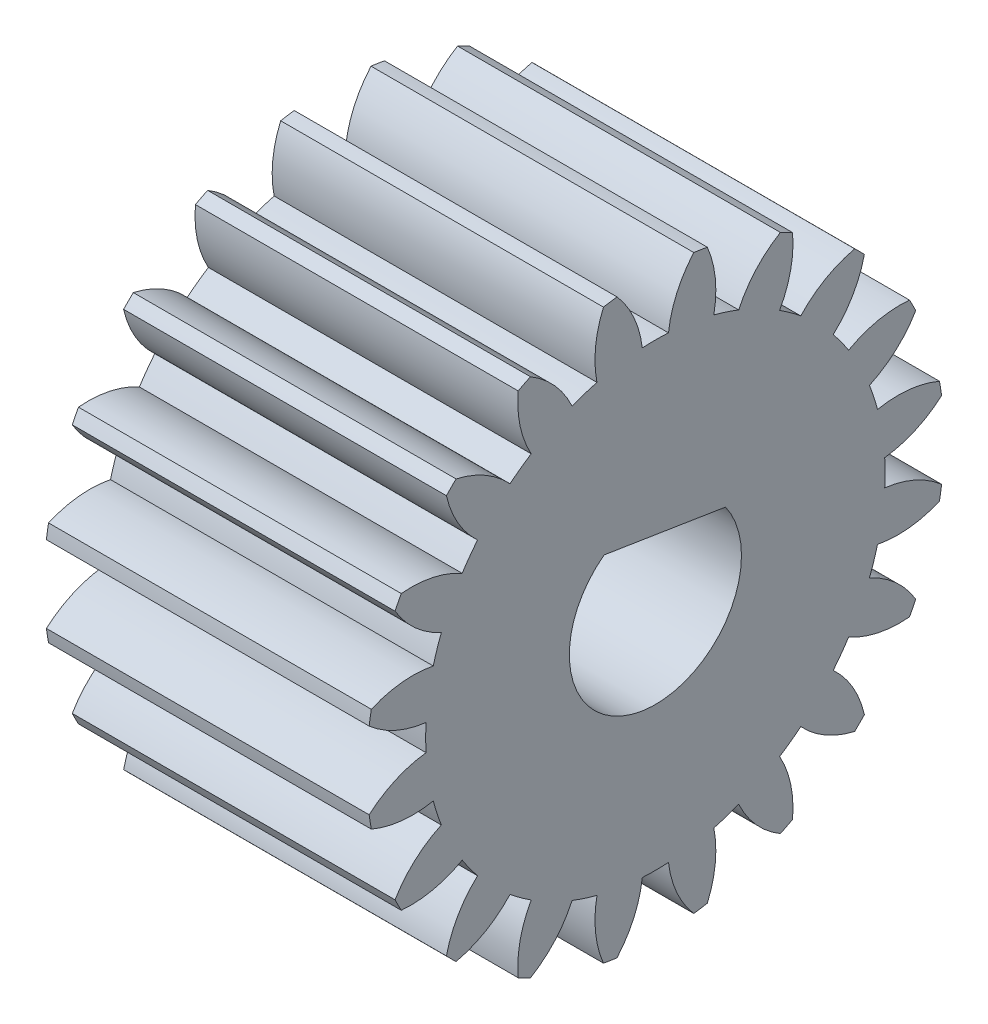
SolidWorks part; units mm, degrees
ref_plane "Plane1" through (0, 0, 0) normal (0, 0, 1) x (1, 0, 0)
ref_plane "Plane2" through (0, 0, 0) normal (0, 1, 0) x (1, 0, 0)
ref_plane "Plane3" through (0, 0, 0) normal (1, 0, 0) x (0, 0, -1)
sketch "HoldingSke" plane through (0, 0, 0) normal (0, 1, 0) x (1, 0, 0)
  line L0 (0, 0) -> (0.7702, -0.2803)
  line L1 (-15, 0) -> (100, 0) construction
  line L2 (0, 0) -> (-2.1039, 2.3779)
  line L3 (0, 0) -> (-11.863, 4.5341)
  line L4 (0, 0) -> (8.1152, 2.9537)
  line L5 (0, 0) -> (-46.8476, -17.4728)
  line L6 (0, 0) -> (-12.4344, -8.3896)
  line L7 (-2.1039, 2.3779) -> (8.6586, 51.2059)
  line L8 (-76.2, 54.61) -> (-74.8, 54.61)
  line L9 (-71.009, 38.7566) -> (-53.1078, 45.2721)
  line L10 (-76.2, 71.12) -> (104.1128, 71.12)
  line L11 (0, 0) -> (-15, 0)
  line L12 (-76.2, 101.6) -> (-76.155, 101.6)
  line L13 (24.9733, 27.94) -> (52.9518, 28.4284)
  line L14 (24.9733, 27.94) -> (24.9743, 27.94)
  line L15 (24.9733, 27.94) -> (100.4006, 29.5858)
  line L16 (-63.627, -1.22) -> (-12.827, -1.22)
  circle A0 centre (0, 0) radius 4
  circle A1 centre (0, 0) radius 10.674
  circle A2 centre (0, 0) radius 37.5
  circle A3 centre (0, 0) radius 4
  dimension "MHD" = 21.348
  dimension "Hub_dia" = 75
  dimension "Bore" = 8
  dimension "MBD" = 8
  dimension "Num_teeth" = 20
  dimension "Pitch" = 0.8197
  dimension "Overall_len" = 50
  dimension "Show_teeth" = 20
  dimension "Thickness" = 15
  dimension "OAL" = 50.0001
  dimension "T_dim" = 1.4
  dimension "Ap" = 20
  dimension "H" = 19.05
  dimension "Pitch_radius" = 180.3128
  dimension "Width" = 15
  dimension "Backlash" = 0.045
  dimension "Addendum_fac" = 1
  dimension "Dedendum_fac" = 1.25
  dimension "Clearance_fac" = 0.25
  dimension "Dedendum_add" = 0.001
  dimension "Module" = 1.22
sketch "BasProSke" plane through (0, 0, 0) normal (0, 1, 0) x (1, 0, 0)
  line L0 (-10, 0) -> (60, 0) construction
  line L1 (0, 0) -> (0, 13.42)
  line L2 (0, 0) -> (15, 0)
  line L3 (15, 0) -> (15, 13.42)
  line L4 (15, 13.42) -> (0, 13.42)
  dimension "Thickness" = 15
  dimension "Diameter" = 26.84
revolve "Base-Revolve" add sketch "BasProSke" angle 360 about L0
sketch "TooCutSke" plane through (0, 0, 0) normal (1, 0, 0) x (0, 0, -1)
  line L1 (0, 0) -> (0, 107) construction
  line L2 (0, 0) -> (-1.0359, 12.1559) construction
  line L3 (0, 0) -> (-3.8071, 24.037) construction
  line L4 (-1.0359, 12.1559) -> (-1.9035, 12.0185) construction
  arc A0 (0.6078, 10.6567) -> (-0.6078, 10.6567) centre (0, 0) ccw
  arc A1 (1.8049, 13.3237) -> (-1.8049, 13.3237) centre (0, 0) ccw
  circle A2 centre (0, 0) radius 12.2 construction
  circle A3 centre (0, 0) radius 11.4642 construction
  arc A4 (-0.6078, 10.6567) -> (-1.8049, 13.3237) centre (-5.4541, 10.0837) ccw
  arc A5 (1.8049, 13.3237) -> (0.6078, 10.6567) centre (5.4541, 10.0837) ccw
  dimension "Root_dia" = 21.348
  dimension "Overcut_dia" = 26.8908
  dimension "Pitch_dia" = 24.4
  dimension "Base_dia" = 22.9285
  dimension "Flank_rad" = 4.88
  dimension "Half_ang" = 9
  dimension "Half_CT" = 0.8785
extrude "ToothCut" cut sketch "TooCutSke" along normal through all
fillet "Breaks" [suppressed] radius 0.0244
fillet "RootFillets" [suppressed] radius 0.306
pattern_circular "TeethCuts" count 20 every 18 about axis through (-10, 0, 0) along (1, 0, 0) of "ToothCut", "RootFillets", "Breaks"
sketch "HubNeaOneSke" plane through (0, 0, 0) normal (-1, 0, 0) x (0, 0, 1)
  circle A0 centre (0, 0) radius 10.674
  dimension "Diameter" = 21.348
extrude "HubNearOne" [suppressed] add sketch "HubNeaOneSke" along normal blind 35.0001
sketch "HubNeaBotSke" plane through (0, 0, 0) normal (-1, 0, 0) x (0, 0, 1)
  circle A0 centre (0, 0) radius 10.674
  dimension "Diameter" = 21.348
extrude "HubNearBoth" [suppressed] add sketch "HubNeaBotSke" along normal blind 17.5
ref_plane "FarPln" through (15, 0, 0) normal (1, 0, 0) x (0, 0, -1)
sketch "HubFarSke" plane through (15, 0, 0) normal (1, 0, 0) x (0, 0, -1)
  circle A0 centre (0, 0) radius 10.674
  dimension "Diameter" = 21.348
extrude "HubFar" [suppressed] add sketch "HubFarSke" along normal blind 17.5
sketch "BorSke" plane through (0, 0, 0) normal (1, 0, 0) x (0, 0, -1)
  circle A0 centre (0, 0) radius 4
  dimension "Diameter" = 8
extrude "Bore" cut sketch "BorSke" along normal mid plane 100.0001
sketch "KeySke" plane through (0, 0, 0) normal (1, 0, 0) x (0, 0, -1)
  line L0 (-1.5, 0) -> (-1.5, 5.4)
  line L1 (-1.5, 5.4) -> (1.5, 5.4)
  line L2 (1.5, 5.4) -> (1.5, 0)
  line L3 (0, 0) -> (0, 34) construction
  line L4 (-1.5, 0) -> (1.5, 0)
  dimension "Offset" = 5.4
  dimension "Width" = 3
extrude "Keyway" [suppressed] cut sketch "KeySke" along normal mid plane 100.0001
pattern_circular "Keyway2" [suppressed] count 2 every 90 about axis through (-10, 0, 0) along (1, 0, 0)
sketch "Sketch1" plane through (0, 0, 0) normal (-1, 0, 0) x (0, 0, 1)
  line L0 (0, 0) -> (0, 4) construction
  line L1 (0, 0) -> (-0.438, 2.7655) construction
  line L2 (-0.438, 2.7655) -> (-0.6257, 3.9508) construction
  line L3 (-3.2594, 2.3187) -> (2.3834, 3.2124)
  circle A0 centre (0, 0) radius 4 construction
  arc A1 (-3.2594, 2.3187) -> (2.3834, 3.2124) centre (0, 0) cw
  point P9 (-0.438, 2.7655)
  dimension "D1" = 8
  dimension "D2" = 9
  dimension "D3" = 1.2
extrude "Boss-Extrude1" add sketch "Sketch1" against normal up to surface (15 mm away) up to face at (15, 0, 4)
sketch "Sketch2" plane through (0, 0, 0) normal (-1, 0, 0) x (0, 0, 1)
  line L0 (0, 0) -> (-7, 0) construction
  line L2 (-7.6, 4) -> (-6.4, 4)
  line L3 (-7.6, 4) -> (-7.6, -4)
  line L4 (-7.6, -4) -> (-6.4, -4)
  line L5 (-6.4, 4) -> (-6.4, -4)
  line L6 (-7.6, 4) -> (-6.4, -4) construction
  line L7 (-7.6, -4) -> (-6.4, 4) construction
  dimension "D1" = 7
  dimension "D2" = 8
  dimension "D3" = 1.2
extrude "Cut-Extrude1" cut sketch "Sketch2" against normal blind 2
equation "' \"Module@HoldingSke\" = 6.35"
equation "' \"Num_teeth@HoldingSke\" = 12"
equation "' \"Ap@HoldingSke\" =  20"
equation "' \"Ap@HoldingSke\" = 20"
equation "' \"Width@HoldingSke\" = 0.5 * 25.4"
equation "' \"Hub_dia@HoldingSke\"= 1 * 25.4"
equation "' \"Hub_dia@HoldingSke\" = 1 * 25.4"
equation "' \"Overall_len@HoldingSke\" = 1.0 * 25.4"
equation "' \"Bore@HoldingSke\" = 0.75 * 25.4"
equation "' \"T_dim@HoldingSke\" = 0.1 * 25.4"
equation "' \"Width@KeySke\" = 0.25 * 25.4"
equation "' \"Show_teeth@HoldingSke\" = 13"
equation "' \"Backlash@HoldingSke\" = 0.009 * 25.4"
equation "' \"Addendum_fac@HoldingSke\" = 1.0"
equation "' \"Dedendum_fac@HoldingSke\" = 1.25"
equation "' \"Dedendum_add@HoldingSke\" = 0.00005 * 25.4"
equation "' \"Clearance_fac@HoldingSke\" = 0.25"
equation "\"Pitch@HoldingSke\" = 1 / \"Module@HoldingSke\""
equation "\"Overcut_dia@TooCutSke\" = (\"Num_teeth@HoldingSke\" + 2 * \"Addendum_fac@HoldingSke\") / \"Pitch@HoldingSke\" + 0.002 * 25.4"
equation "\"Pitch_dia@TooCutSke\" = \"Num_teeth@HoldingSke\" / \"Pitch@HoldingSke\""
equation "\"Base_dia@TooCutSke\" = \"Num_teeth@HoldingSke\" / \"Pitch@HoldingSke\" * cos((\"Ap@HoldingSke\"  * 3.14159265 / 180))"
equation "\"Root_dia@TooCutSke\" = (\"Num_teeth@HoldingSke\" + 2) / \"Pitch@HoldingSke\" - 2 * (\"Addendum_fac@HoldingSke\" + \"Dedendum_fac@HoldingSke\") / \"Pitch@HoldingSke\" - \"Dedendum_add@HoldingSke\" * 2"
equation "\"Half_ang@TooCutSke\" = 180 / \"Num_teeth@HoldingSke\""
equation "\"Half_CT@TooCutSke\" = \"Num_teeth@HoldingSke\" / \"Pitch@HoldingSke\" * sin((3.14159265 / 2 / \"Num_teeth@HoldingSke\")) / 2 - 7 * \"Backlash@HoldingSke\" / 4"
equation "\"Flank_rad@TooCutSke\" = \"Num_teeth@HoldingSke\" / \"Pitch@HoldingSke\" / 5"
equation "\"Radius@RootFillets\" = \"Clearance_fac@HoldingSke\" / \"Pitch@HoldingSke\" + \"Dedendum_add@HoldingSke\""
equation "\"Break_rad@Breaks\" = 0.02 / \"Pitch@HoldingSke\""
equation "\"Thickness@HoldingSke\" = \"Width@HoldingSke\""
equation "\"OAL@HoldingSke\" = \"Thickness@HoldingSke\""
equation "\"MHD@HoldingSke\" = (\"Num_teeth@HoldingSke\" + 2) / \"Pitch@HoldingSke\" - 2 * (\"Addendum_fac@HoldingSke\" + \"Dedendum_fac@HoldingSke\")  / \"Pitch@HoldingSke\" - \"Dedendum_add@HoldingSke\" * 2"
equation "\"MBD@HoldingSke\" = (\"Num_teeth@HoldingSke\" + 2) / \"Pitch@HoldingSke\" - 2 * (\"Addendum_fac@HoldingSke\" + \"Dedendum_fac@HoldingSke\")  / \"Pitch@HoldingSke\" - \"Dedendum_add@HoldingSke\" * 2 - 0.002 * 25.4"
equation "\"MHD@HoldingSke\" = ((sgn( \"MHD@HoldingSke\" - \"Hub_dia@HoldingSke\" )-1)*( \"MHD@HoldingSke\" - \"Hub_dia@HoldingSke\" ))/-2+ \"Hub_dia@HoldingSke\""
equation "\"MBD@HoldingSke\" = ((sgn( \"MBD@HoldingSke\" - \"Bore@HoldingSke\" )-1)*( \"MBD@HoldingSke\" - \"Bore@HoldingSke\" ))/-2+ \"Bore@HoldingSke\""
equation "\"OAL@HoldingSke\" = ((sgn( \"OAL@HoldingSke\" - \"Overall_len@HoldingSke\" )+1)*( \"OAL@HoldingSke\" - \"Overall_len@HoldingSke\" ))/2 + \"Overall_len@HoldingSke\" + 0.000002 * 25.4"
equation "\"Num_teeth@TeethCuts\" = int( \"Show_teeth@HoldingSke\" ) + 1"
equation "\"Num_teeth@TeethCuts\" = ((sgn( \"Num_teeth@TeethCuts\" - \"Num_teeth@HoldingSke\" )-1)*( \"Num_teeth@TeethCuts\" - \"Num_teeth@HoldingSke\" ))/-2+ \"Num_teeth@HoldingSke\""
equation "\"Num_teeth@TeethCuts\" = ((sgn( \"Num_teeth@TeethCuts\" - 2.0)+1)*( \"Num_teeth@TeethCuts\" - 2.0))/2 +2.0"
equation "\"Angle@TeethCuts\" = 360.0 / \"Num_teeth@HoldingSke\""
equation "\"Diameter@BasProSke\" = (\"Num_teeth@HoldingSke\" + 2 * \"Addendum_fac@HoldingSke\") / \"Pitch@HoldingSke\""
equation "\"Thickness@BasProSke\"  = \"Thickness@HoldingSke\""
equation "' \"Fillet_rad@BasProSke\" =  \"Thickness@HoldingSke\" * 0.05"
equation "' \"Fillet_rad@BasProSke\" = \"Thickness@HoldingSke\" * 0.05"
equation "\"MHD@HoldingSke\" = ((sgn( \"MHD@HoldingSke\" - \"Root_dia@TooCutSke\" )-1)*( \"MHD@HoldingSke\" - \"Root_dia@TooCutSke\" ))/-2+ \"Root_dia@TooCutSke\""
equation "\"Diameter@HubNeaOneSke\" = \"MHD@HoldingSke\""
equation "\"Length@HubNearOne\" = \"OAL@HoldingSke\" - \"Thickness@BasProSke\""
equation "\"Diameter@HubNeaBotSke\" = \"MHD@HoldingSke\""
equation "\"Length@HubNearBoth\" = ( \"OAL@HoldingSke\" - \"Thickness@BasProSke\" ) / 2.0"
equation "\"Thickness@FarPln\" = \"Thickness@BasProSke\""
equation "\"Diameter@HubFarSke\" = \"MHD@HoldingSke\""
equation "\"Length@HubFar\" = ( \"OAL@HoldingSke\" - \"Thickness@BasProSke\" ) / 2.0"
equation "\"Diameter@BorSke\" = \"MBD@HoldingSke\""
equation "\"D1@Bore\" = \"OAL@HoldingSke\" * 2.0"
equation "\"D1@Keyway\" = \"OAL@HoldingSke\" * 2.0"
equation "\"Offset@KeySke\" = \"T_dim@HoldingSke\" + \"MBD@HoldingSke\" / 2.0"
